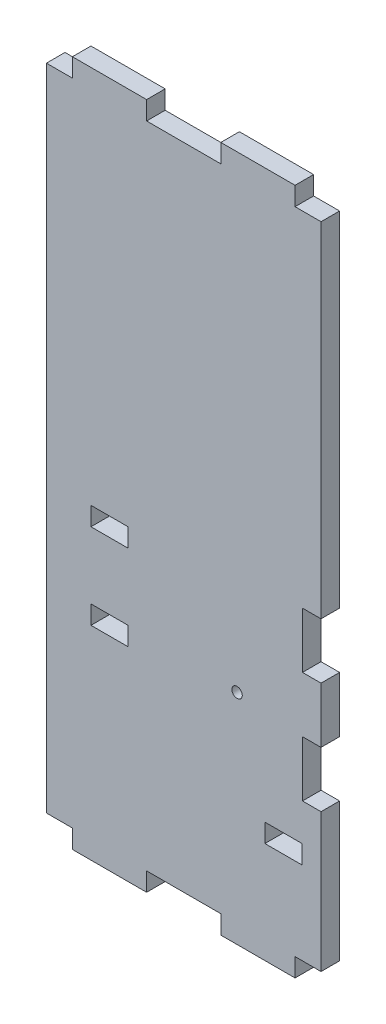
SolidWorks part; units mm, degrees
material "Maple"
ref_plane "Front Plane" through (0, 0, 0) normal (0, 0, 1) x (1, 0, 0)
ref_plane "Top Plane" through (0, 0, 0) normal (0, 1, 0) x (1, 0, 0)
ref_plane "Right Plane" through (0, 0, 0) normal (1, 0, 0) x (0, 0, -1)
sketch "Sketch1" plane through (0, 0, 0) normal (0, 0, 1) x (1, 0, 0)
  line L0 (0, -111.125) -> (0, 111.125) construction
  line L1 (46.99, -111.125) -> (-46.99, -111.125) construction
  line L2 (46.99, -111.125) -> (46.99, 111.125) construction
  line L3 (46.99, 111.125) -> (-46.99, 111.125) construction
  line L4 (-46.99, -111.125) -> (-46.99, 111.125) construction
  line L5 (46.99, -111.125) -> (-46.99, 111.125) construction
  line L6 (46.99, 111.125) -> (-46.99, -111.125) construction
  line L7 (-38.1, 117.475) -> (-12.7, 111.125) construction
  line L8 (-38.1, 111.125) -> (-12.7, 111.125) construction
  line L9 (-38.1, 111.125) -> (-38.1, 117.475) construction
  line L10 (-38.1, 117.475) -> (-12.7, 117.475) construction
  line L11 (-12.7, 111.125) -> (-12.7, 117.475) construction
  line L12 (-35.1261, -111.125) -> (-8.4459, -111.125) construction
  line L16 (46.99, 0) -> (-46.99, 0) construction
  line L17 (38.1, 111.125) -> (38.1, 117.475) construction
  line L18 (12.7, 111.125) -> (12.7, 117.475) construction
  line L19 (38.1, 117.475) -> (12.7, 117.475) construction
  line L20 (-38.1, -111.125) -> (-38.1, -117.475) construction
  line L21 (-38.1, -117.475) -> (-12.7, -117.475) construction
  line L22 (-12.7, -111.125) -> (-12.7, -117.475) construction
  line L23 (12.7, -111.125) -> (12.7, -117.475) construction
  line L24 (38.1, -117.475) -> (12.7, -117.475) construction
  line L25 (38.1, -111.125) -> (38.1, -117.475) construction
  line L26 (-46.99, 111.125) -> (-38.1, 111.125)
  line L27 (-38.1, 111.125) -> (-38.1, 117.475)
  line L28 (-38.1, 117.475) -> (-12.7, 117.475)
  line L29 (-12.7, 117.475) -> (-12.7, 111.125)
  line L30 (-12.7, 111.125) -> (12.7, 111.125)
  line L31 (12.7, 111.125) -> (12.7, 117.475)
  line L32 (12.7, 117.475) -> (38.1, 117.475)
  line L33 (38.1, 117.475) -> (38.1, 111.125)
  line L34 (38.1, 111.125) -> (46.99, 111.125)
  line L35 (46.99, 111.125) -> (46.99, -111.125)
  line L36 (46.99, -111.125) -> (38.1, -111.125)
  line L37 (38.1, -111.125) -> (38.1, -117.475)
  line L38 (38.1, -117.475) -> (12.7, -117.475)
  line L39 (12.7, -117.475) -> (12.7, -111.125)
  line L40 (12.7, -111.125) -> (-12.7, -111.125)
  line L41 (-12.7, -111.125) -> (-12.7, -117.475)
  line L42 (-12.7, -117.475) -> (-38.1, -117.475)
  line L43 (-38.1, -117.475) -> (-38.1, -111.125)
  line L44 (-38.1, -111.125) -> (-46.99, -111.125)
  line L45 (-46.99, -111.125) -> (-46.99, 111.125)
  point P0 (0, 0)
  point P9 (0, 0)
  point P17 (-25.4, 114.3)
  point P20 (0, 0)
  dimension "D1" = 93.98
  dimension "D2" = 222.25
  dimension "D3" = 6.35
  dimension "D4" = 25.4
  dimension "D5" = 25.4
extrude "Boss-Extrude1" add sketch "Sketch1" along normal blind 6.35
sketch "Sketch2" plane through (0, 0, 0) normal (0, 0, -1) x (-1, 0, 0)
  line L0 (0, 111.125) -> (0, -111.125) construction
  line L1 (-12.7, 111.125) -> (12.7, 111.125) construction
  line L2 (12.7, -111.125) -> (-12.7, -111.125) construction
  line L3 (-4.572, 111.125) -> (-4.572, -111.125) construction
  line L4 (-46.99, 111.125) -> (46.99, 111.125) construction
  line L5 (0, -73.025) -> (-8.89, -73.025) construction
  line L6 (0, -73.025) -> (0, -66.675) construction
  line L7 (0, -66.675) -> (-8.89, -66.675) construction
  line L8 (-8.89, -73.025) -> (-8.89, -66.675) construction
  line L9 (-46.99, -111.125) -> (46.99, -111.125) construction
  line L10 (-18.2562, 111.125) -> (-18.2562, -111.125) construction
  line L11 (-4.445, -66.675) -> (-18.2562, -42.7532) construction
  line L12 (-23.7555, -45.9282) -> (-12.757, -39.5782) construction
  line L13 (-42.8055, -12.9326) -> (-31.807, -6.5826) construction
  line L14 (-42.8055, -12.9326) -> (-11.0555, -67.9253) construction
  line L15 (-11.0555, -67.9253) -> (-0.057, -61.5753) construction
  line L16 (-31.807, -6.5826) -> (-0.057, -61.5753) construction
  line L17 (-39.6305, -18.4319) -> (-28.632, -12.0819) construction
  line L18 (19.05, -24.7819) -> (31.75, -24.7819) construction
  line L19 (19.05, -18.6605) -> (31.75, -18.6605) construction
  line L20 (19.05, -18.6605) -> (19.05, -41.5205) construction
  line L21 (19.05, -41.5205) -> (31.75, -41.5205) construction
  line L22 (31.75, -18.6605) -> (31.75, -41.5205) construction
  line L23 (19.05, -18.6605) -> (31.75, -41.5205) construction
  line L24 (19.05, -41.5205) -> (31.75, -18.6605) construction
  line L25 (-46.99, -111.125) -> (-46.99, 111.125) construction
  line L26 (19.05, -18.6605) -> (31.75, -18.6605)
  line L27 (19.05, -18.6605) -> (19.05, -12.3105)
  line L28 (19.05, -12.3105) -> (31.75, -12.3105)
  line L29 (31.75, -18.6605) -> (31.75, -12.3105)
  line L30 (19.05, -41.5205) -> (31.75, -41.5205)
  line L31 (19.05, -41.5205) -> (19.05, -47.8705)
  line L32 (19.05, -47.8705) -> (31.75, -47.8705)
  line L33 (31.75, -41.5205) -> (31.75, -47.8705)
  line L34 (-46.99, -6.5826) -> (-40.64, -6.5826)
  line L35 (-46.99, -6.5826) -> (-46.99, -25.6326)
  line L36 (-46.99, -25.6326) -> (-40.64, -25.6326)
  line L37 (-40.64, -6.5826) -> (-40.64, -25.6326)
  line L38 (-18.2562, -42.7532) -> (25.4, -42.7532) construction
  line L39 (-34.1312, -15.2569) -> (-34.1312, -111.125) construction
  line L41 (-40.4812, -76.4326) -> (-27.7812, -76.4326)
  line L42 (-40.4812, -76.4326) -> (-40.4812, -82.7826)
  line L43 (-40.4812, -82.7826) -> (-27.7812, -82.7826)
  line L44 (-27.7812, -76.4326) -> (-27.7812, -82.7826)
  line L45 (-40.4812, -76.4326) -> (-27.7812, -82.7826) construction
  line L46 (-40.4812, -82.7826) -> (-27.7812, -76.4326) construction
  line L47 (-46.99, -44.6826) -> (-40.64, -44.6826)
  line L48 (-46.99, -44.6826) -> (-46.99, -63.7326)
  line L49 (-46.99, -63.7326) -> (-40.64, -63.7326)
  line L50 (-40.64, -44.6826) -> (-40.64, -63.7326)
  circle A0 centre (-18.2562, -42.7532) radius 1.778
  point P28 (-34.1312, -15.2569)
  point P32 (-18.2562, -42.7532)
  point P35 (25.4, -30.0905)
  point P40 (25.4, -42.7532)
  point P56 (-34.1312, -79.6076)
  point P66 (-34.1312, -79.6076)
  line M17 (-46.99, 111.125) -> (-46.99, -111.125)
  dimension "D10" = 3.556
  dimension "D1" = 4.572
  dimension "D2" = 8.89
  dimension "D3" = 6.35
  dimension "D4" = 38.1
  dimension "D5" = 30
  dimension "D6" = 12.7
  dimension "D7" = 25.4
  dimension "D8" = 38.1
  dimension "D9" = 6.35
  dimension "D11" = 22.86
  dimension "D12" = 12.7
  dimension "D13" = 6.1214
  dimension "D14" = 6.35
  dimension "D15" = 6.35
  dimension "D16" = 25.4
  dimension "D17" = 6.35
  dimension "D18" = 6.35
  dimension "D19" = 19.05
  dimension "D20" = 76.2
  dimension "D21" = 19.05
  dimension "D22" = 6.35
  dimension "D23" = 19.05
  dimension "D24" = 6.35
  dimension "D25" = 12.7
  dimension "D26" = 9.525
  dimension "D27" = 57.15
extrude "Cut-Extrude1" cut sketch "Sketch2" against normal through all contours L50 L47 L49 M17 | L37 L34 L36 M17 | L44 L41 L42 L43 | L27 L26 L29 L28 | L31 L30 L33 L32 | A0
sketch "Sketch3" plane through (0, 0, 0) normal (0, 0, -1) x (-1, 0, 0)
  line L0 (-40.386, -25.8866) -> (-46.736, -25.8866)
  line L1 (-46.736, -25.8866) -> (-46.736, -44.4286)
  line L2 (-46.736, -44.4286) -> (-40.386, -44.4286)
  line L3 (-40.386, -44.4286) -> (-40.386, -63.9866)
  line L4 (-40.386, -63.9866) -> (-46.736, -63.9866)
  line L5 (-46.736, -63.9866) -> (-46.736, -110.871)
  line L6 (-46.736, -110.871) -> (-37.846, -110.871)
  line L7 (-37.846, -110.871) -> (-37.846, -117.221)
  line L8 (-37.846, -117.221) -> (-12.954, -117.221)
  line L9 (-12.954, -117.221) -> (-12.954, -110.871)
  line L10 (-12.954, -110.871) -> (12.954, -110.871)
  line L11 (12.954, -110.871) -> (12.954, -117.221)
  line L12 (12.954, -117.221) -> (37.846, -117.221)
  line L13 (37.846, -117.221) -> (37.846, -110.871)
  line L14 (37.846, -110.871) -> (46.736, -110.871)
  line L15 (46.736, -110.871) -> (46.736, 110.871)
  line L16 (46.736, 110.871) -> (37.846, 110.871)
  line L17 (37.846, 110.871) -> (37.846, 117.221)
  line L18 (37.846, 117.221) -> (12.954, 117.221)
  line L19 (12.954, 117.221) -> (12.954, 110.871)
  line L20 (12.954, 110.871) -> (-12.954, 110.871)
  line L21 (-12.954, 110.871) -> (-12.954, 117.221)
  line L22 (-12.954, 117.221) -> (-37.846, 117.221)
  line L23 (-37.846, 117.221) -> (-37.846, 110.871)
  line L24 (-37.846, 110.871) -> (-46.736, 110.871)
  line L25 (-46.736, 110.871) -> (-46.736, -6.3286)
  line L26 (-46.736, -6.3286) -> (-40.386, -6.3286)
  line L27 (-40.386, -6.3286) -> (-40.386, -25.8866)
  line L28 (-40.64, -25.6326) -> (-46.99, -25.6326)
  line L29 (-46.99, -25.6326) -> (-46.99, -44.6826)
  line L30 (-46.99, -44.6826) -> (-40.64, -44.6826)
  line L31 (-40.64, -44.6826) -> (-40.64, -63.7326)
  line L32 (-40.64, -63.7326) -> (-46.99, -63.7326)
  line L33 (-46.99, -63.7326) -> (-46.99, -111.125)
  line L34 (-46.99, -111.125) -> (-38.1, -111.125)
  line L35 (-38.1, -111.125) -> (-38.1, -117.475)
  line L36 (-38.1, -117.475) -> (-12.7, -117.475)
  line L37 (-12.7, -117.475) -> (-12.7, -111.125)
  line L38 (-12.7, -111.125) -> (12.7, -111.125)
  line L39 (12.7, -111.125) -> (12.7, -117.475)
  line L40 (12.7, -117.475) -> (38.1, -117.475)
  line L41 (38.1, -117.475) -> (38.1, -111.125)
  line L42 (38.1, -111.125) -> (46.99, -111.125)
  line L43 (46.99, -111.125) -> (46.99, 111.125)
  line L44 (46.99, 111.125) -> (38.1, 111.125)
  line L45 (38.1, 111.125) -> (38.1, 117.475)
  line L46 (38.1, 117.475) -> (12.7, 117.475)
  line L47 (12.7, 117.475) -> (12.7, 111.125)
  line L48 (12.7, 111.125) -> (-12.7, 111.125)
  line L49 (-12.7, 111.125) -> (-12.7, 117.475)
  line L50 (-12.7, 117.475) -> (-38.1, 117.475)
  line L51 (-38.1, 117.475) -> (-38.1, 111.125)
  line L52 (-38.1, 111.125) -> (-46.99, 111.125)
  line L53 (-46.99, 111.125) -> (-46.99, -6.5826)
  line L54 (-46.99, -6.5826) -> (-40.64, -6.5826)
  line L55 (-40.64, -6.5826) -> (-40.64, -25.6326)
  line L56 (-40.64, -25.6326) -> (-46.99, -25.6326) construction
  line L57 (-46.99, -25.6326) -> (-46.99, -44.6826) construction
  line L58 (-46.99, -44.6826) -> (-40.64, -44.6826) construction
  line L59 (-40.64, -44.6826) -> (-40.64, -63.7326) construction
  line L60 (-40.64, -63.7326) -> (-46.99, -63.7326) construction
  line L61 (-46.99, -63.7326) -> (-46.99, -111.125) construction
  line L62 (-46.99, -111.125) -> (-38.1, -111.125) construction
  line L63 (-38.1, -111.125) -> (-38.1, -117.475) construction
  line L64 (-38.1, -117.475) -> (-12.7, -117.475) construction
  line L65 (-12.7, -117.475) -> (-12.7, -111.125) construction
  line L66 (-12.7, -111.125) -> (12.7, -111.125) construction
  line L67 (12.7, -111.125) -> (12.7, -117.475) construction
  line L68 (12.7, -117.475) -> (38.1, -117.475) construction
  line L69 (38.1, -117.475) -> (38.1, -111.125) construction
  line L70 (38.1, -111.125) -> (46.99, -111.125) construction
  line L71 (46.99, -111.125) -> (46.99, 111.125) construction
  line L72 (46.99, 111.125) -> (38.1, 111.125) construction
  line L73 (38.1, 111.125) -> (38.1, 117.475) construction
  line L74 (38.1, 117.475) -> (12.7, 117.475) construction
  line L75 (12.7, 117.475) -> (12.7, 111.125) construction
  line L76 (12.7, 111.125) -> (-12.7, 111.125) construction
  line L77 (-12.7, 111.125) -> (-12.7, 117.475) construction
  line L78 (-12.7, 117.475) -> (-38.1, 117.475) construction
  line L79 (-38.1, 117.475) -> (-38.1, 111.125) construction
  line L80 (-38.1, 111.125) -> (-46.99, 111.125) construction
  line L81 (-46.99, 111.125) -> (-46.99, -6.5826) construction
  line L82 (-46.99, -6.5826) -> (-40.64, -6.5826) construction
  line L83 (-40.64, -6.5826) -> (-40.64, -25.6326) construction
  line L85 (-232.8801, 251.2145) -> (196.3669, 251.2145)
  line L86 (-232.8801, 251.2145) -> (-232.8801, -263.7302)
  line L87 (-232.8801, -263.7302) -> (196.3669, -263.7302)
  line L88 (196.3669, 251.2145) -> (196.3669, -263.7302)
  dimension "D1" = 0
  dimension "D2" = 0.254
extrude "Cut-Extrude2" [suppressed] cut sketch "Sketch3" against normal through all
